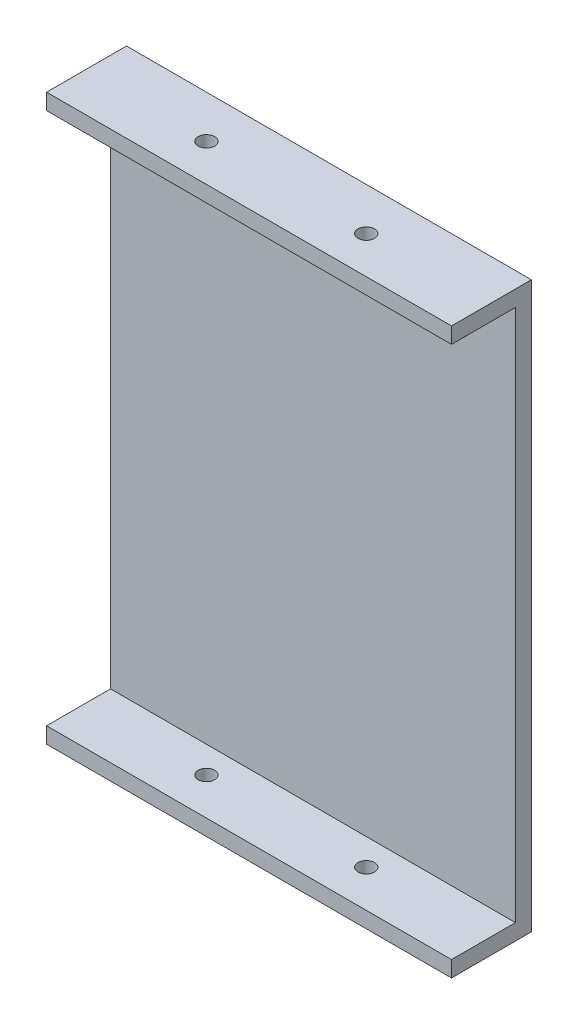
SolidWorks part; units mm, degrees
material "Thornel Mat VMA"
ref_plane "前视基准面" through (0, 0, 0) normal (0, 0, 1) x (1, 0, 0)
ref_plane "上视基准面" through (0, 0, 0) normal (0, 1, 0) x (1, 0, 0)
ref_plane "右视基准面" through (0, 0, 0) normal (1, 0, 0) x (0, 0, -1)
other "Configuration Table"
sketch "草图1" plane through (0, 0, 0) normal (0, 0, 1) x (1, 0, 0)
  line L0 (0, 10) -> (76, 10) construction
  line L1 (0, 0) -> (76, 0)
  line L2 (0, 0) -> (0, 190)
  line L3 (0, 190) -> (76, 190)
  line L4 (76, 0) -> (76, 190)
  line L5 (0, 180) -> (76, 180) construction
  line L6 (38, 10) -> (38, 180) construction
  circle A1 centre (63, 10) radius 1.55
  circle A2 centre (13, 10) radius 1.55
  circle A4 centre (63, 180) radius 1.55
  circle A5 centre (13, 180) radius 1.55
  dimension "D5" = 3.1
  dimension "D7" = 3.1
  dimension "D9" = 3.1
  dimension "D10" = 3.1
  dimension "D1" = 76
  dimension "D2" = 190
  dimension "D3" = 10
  dimension "D4" = 10
  dimension "D11" = 25
  dimension "D12" = 25
  dimension "D13" = 25
  dimension "D14" = 25
extrude "凸台-拉伸1" add sketch "草图1" along normal blind 3
sketch "草图2" plane through (0, 0, 3) normal (0, 0, 1) x (1, 0, 0)
  line L0 (0, 190) -> (0, 0) construction
  line L1 (0, 45) -> (76, 45)
  line L2 (0, 45) -> (0, 42)
  line L3 (0, 42) -> (76, 42)
  line L4 (76, 45) -> (76, 42)
  line L5 (76, 0) -> (76, 190) construction
  line L6 (0, 95) -> (76, 95) construction
  line L7 (0, 148) -> (76, 148)
  line L8 (0, 148) -> (0, 145)
  line L9 (0, 145) -> (76, 145)
  line L10 (76, 148) -> (76, 145)
  dimension "D1" = 50
  dimension "D2" = 50
  dimension "D3" = 3
  dimension "D4" = 3
extrude "凸台-拉伸2" add sketch "草图2" along normal blind 12
sketch "草图3" plane through (0, 42, 0) normal (0, -1, 0) x (1, 0, 0)
  line L0 (38, 15) -> (38, 3) construction
  line L1 (0, 15) -> (76, 15) construction
  line L2 (0, 3) -> (76, 3) construction
  line L3 (0, 3) -> (76, 3) construction
  circle A0 centre (23, 8) radius 1.55
  circle A1 centre (53, 8) radius 1.55
  dimension "D5" = 3.1
  dimension "D6" = 3.1
  dimension "D1" = 15
  dimension "D2" = 15
  dimension "D3" = 5
  dimension "D4" = 5
extrude "切除-拉伸1" cut sketch "草图3" against normal through all
sketch "草图4" plane through (0, 0, 3) normal (0, 0, 1) x (1, 0, 0)
  line L1 (0, 42) -> (76, 42)
  line L2 (0, 42) -> (0, 0)
  line L3 (0, 0) -> (76, 0)
  line L4 (76, 42) -> (76, 0)
  line L5 (76, 148) -> (0, 148)
  line L6 (76, 148) -> (76, 190)
  line L7 (76, 190) -> (0, 190)
  line L8 (0, 148) -> (0, 190)
extrude "切除-拉伸2" cut sketch "草图4" against normal blind 10
